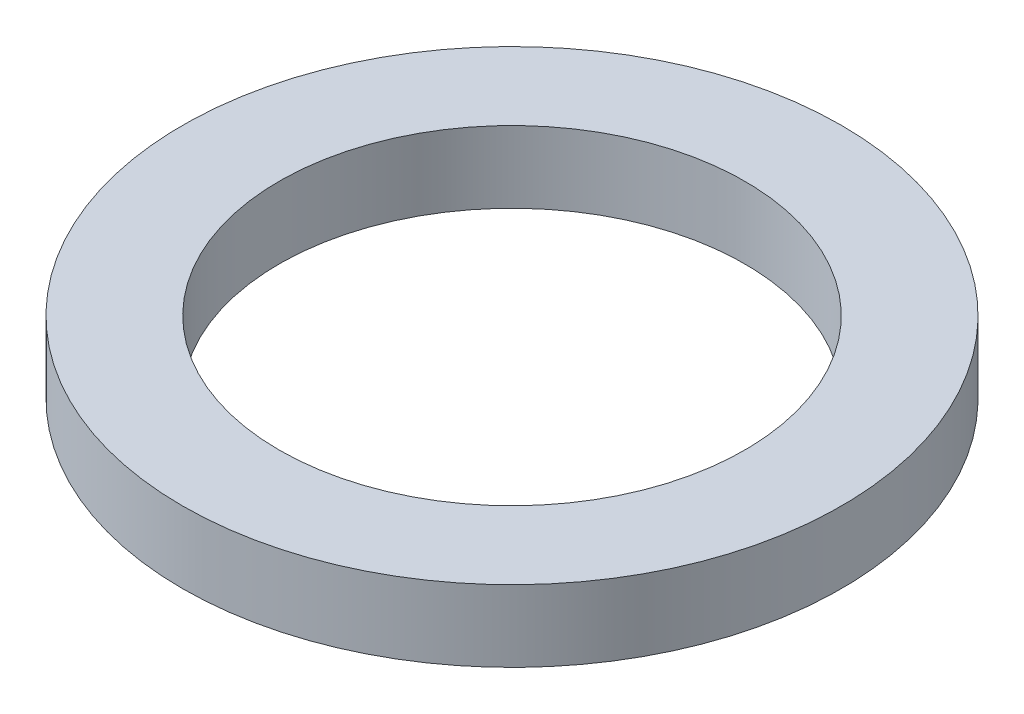
SolidWorks part; units mm, degrees
ref_plane "Front Plane" through (0, 0, 0) normal (0, 0, 1) x (1, 0, 0)
ref_plane "Top Plane" through (0, 0, 0) normal (0, 1, 0) x (1, 0, 0)
ref_plane "Right Plane" through (0, 0, 0) normal (1, 0, 0) x (0, 0, -1)
sketch "Sketch1" plane through (0, 0, 0) normal (0, 1, 0) x (1, 0, 0)
  circle A0 centre (0, 0) radius 20.6375
  circle A1 centre (0, 0) radius 29.21
  dimension "D1" = 58.42
  dimension "D2" = 41.275
extrude "Boss-Extrude1" add sketch "Sketch1" along normal blind 6.35
